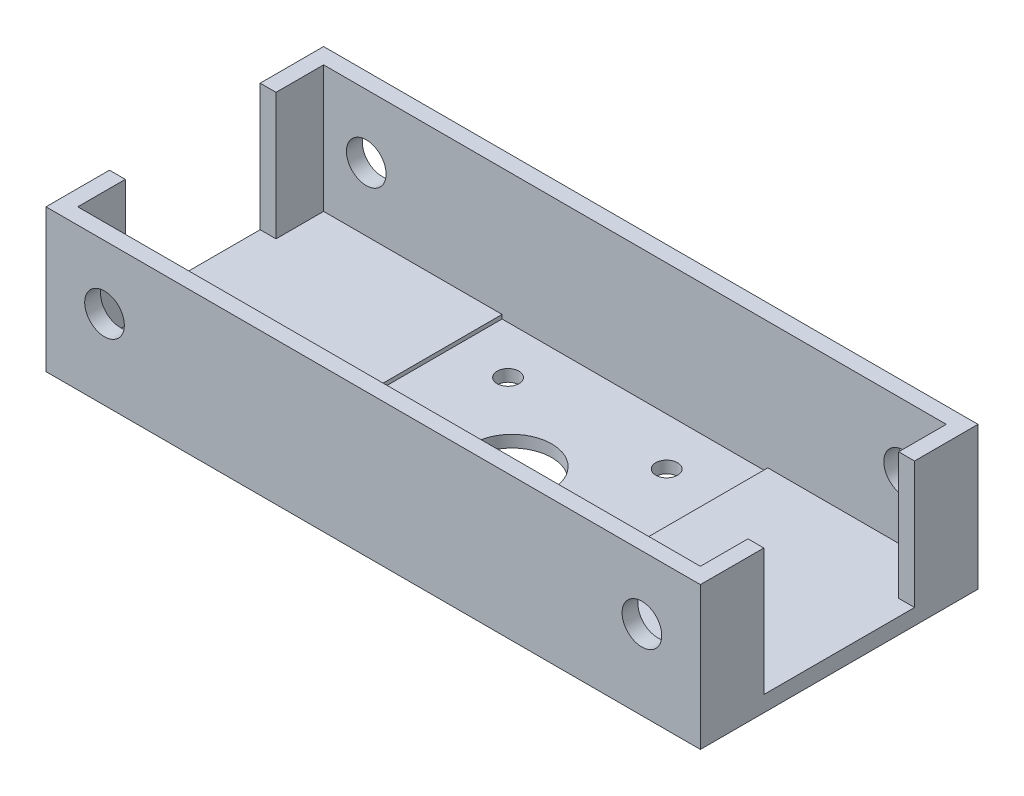
SolidWorks part; units mm, degrees
ref_plane "Front Plane" through (0, 0, 0) normal (0, 0, 1) x (1, 0, 0)
ref_plane "Top Plane" through (0, 0, 0) normal (0, 1, 0) x (1, 0, 0)
ref_plane "Right Plane" through (0, 0, 0) normal (1, 0, 0) x (0, 0, -1)
sketch "Sketch1" plane through (0, 0, 0) normal (0, 1, 0) x (1, 0, 0)
  line L0 (0, 0) -> (0, -14.43) construction
  line L1 (-37.5, 20) -> (37.5, 20)
  line L2 (-37.5, 20) -> (-37.5, -20)
  line L3 (-37.5, -20) -> (37.5, -20)
  line L4 (37.5, 20) -> (37.5, -20)
  line L5 (-37.5, 20) -> (37.5, -20) construction
  line L6 (-37.5, -20) -> (37.5, 20) construction
  line L7 (0, 0) -> (6.508, 0) construction
  line L8 (-5, 10) -> (5, 10)
  line L9 (-5, 10) -> (-5, -10)
  line L10 (-5, -10) -> (5, -10)
  line L11 (5, 10) -> (5, -10)
  line L12 (-5, 10) -> (5, -10) construction
  line L13 (-5, -10) -> (5, 10) construction
  circle A0 centre (-21, 0) radius 5
  circle A1 centre (-30, 8.25) radius 1.7
  circle A2 centre (-12, 8.25) radius 1.7
  circle A3 centre (-12, -8.25) radius 1.7
  circle A4 centre (-30, -8.25) radius 1.7
  circle A5 centre (12, 8.25) radius 1.7
  circle A6 centre (12, -8.25) radius 1.7
  circle A7 centre (21, 0) radius 5
  circle A8 centre (30, -8.25) radius 1.7
  circle A9 centre (30, 8.25) radius 1.7
  point P0 (0, 0)
  dimension "D3" = 10
  dimension "D4" = 16.5
  dimension "D5" = 16.5
  dimension "D6" = 18
  dimension "D9" = 10
  dimension "D11" = 20
  dimension "D13" = 7.5
  dimension "D17" = 3.4
  dimension "D19" = 11.75
  dimension "D20" = 11.75
  dimension "D1" = 75
  dimension "D2" = 40
  dimension "D10" = 10
  dimension "D7" = 2
  dimension "D8" = 2
extrude "Boss-Extrude1" add sketch "Sketch1" along normal blind 3
sketch "Sketch2" plane through (0, 3, 0) normal (0, 1, 0) x (1, 0, 0)
  line L0 (-37.5, 20) -> (-37.5, -20) construction
  line L1 (-33.5, 14) -> (33.5, 14)
  line L2 (-33.5, 14) -> (-33.5, -14)
  line L3 (-33.5, -14) -> (33.5, -14)
  line L4 (33.5, 14) -> (33.5, -14)
  line L5 (37.5, -20) -> (37.5, 20) construction
  line L6 (37.5, 20) -> (-37.5, 20) construction
  line L7 (-37.5, -20) -> (37.5, -20) construction
  dimension "D1" = 4
  dimension "D2" = 4
  dimension "D3" = 6
  dimension "D4" = 6
extrude "Cut-Extrude1" cut sketch "Sketch2" against normal through all both and the other way through all
sketch "Sketch3" plane through (0, 3, 0) normal (0, 1, 0) x (1, 0, 0)
  line L1 (37.5, 20) -> (-37.5, 20)
  line L2 (37.5, 20) -> (37.5, 35)
  line L3 (37.5, 35) -> (-37.5, 35)
  line L4 (-37.5, 20) -> (-37.5, 35)
  line L5 (-37.5, -20) -> (37.5, -20)
  line L6 (-37.5, -20) -> (-37.5, -35)
  line L7 (-37.5, -35) -> (37.5, -35)
  line L8 (37.5, -20) -> (37.5, -35)
  line L10 (-37.5, 20) -> (-33.5, 20)
  line L11 (-37.5, 20) -> (-37.5, -20)
  line L12 (-37.5, -20) -> (-33.5, -20)
  line L13 (-33.5, 20) -> (-33.5, -20)
  line L14 (37.5, 20) -> (33.5, 20)
  line L15 (37.5, 20) -> (37.5, -20)
  line L16 (37.5, -20) -> (33.5, -20)
  line L17 (33.5, 20) -> (33.5, -20)
  line M3 (-33.5, -14) -> (-33.5, 14)
  line M5 (33.5, 14) -> (33.5, -14)
  line M11 (37.5, -20) -> (37.5, 20)
  line M12 (37.5, 20) -> (-37.5, 20)
  line M13 (-37.5, 20) -> (-37.5, -20)
  line M14 (-37.5, -20) -> (37.5, -20)
  dimension "D1" = 15
  dimension "D2" = 15
extrude "Boss-Extrude3" add sketch "Sketch3" along normal blind 110 and the other way blind 3 contours L8 L5 L6 L7 M14 | L4 L1 L2 L3 M12 | L17 M12 M5 M14 M11 | L13 L1 M13 M14 M3
sketch "Sketch6" plane through (0, 3, 0) normal (0, 1, 0) x (1, 0, 0)
  line L0 (-37.5, -35) -> (37.5, -35) construction
  line L1 (-33.5, -20) -> (33.5, -20)
  line L2 (-33.5, -20) -> (-33.5, -31)
  line L3 (-33.5, -31) -> (33.5, -31)
  line L4 (33.5, -20) -> (33.5, -31)
  line L5 (33.5, 20) -> (-33.5, 20)
  line L6 (33.5, 20) -> (33.5, 31)
  line L7 (33.5, 31) -> (-33.5, 31)
  line L8 (-33.5, 20) -> (-33.5, 31)
  line L9 (37.5, 35) -> (-37.5, 35) construction
  dimension "D1" = 4
  dimension "D2" = 4
extrude "Cut-Extrude4" cut sketch "Sketch6" along normal through all
sketch "Sketch7" plane through (-37.5, 0, 0) normal (-1, 0, 0) x (0, 0, 1)
  line L0 (35, 0) -> (35, 113) construction
  line L1 (-35, 113) -> (35, 113)
  line L2 (-35, 113) -> (-35, 76)
  line L3 (-35, 76) -> (35, 76)
  line L4 (35, 113) -> (35, 76)
  dimension "D1" = 37
extrude "Boss-Extrude4" add sketch "Sketch7" along normal blind 45
ref_plane "Plane1" through (0, 0, 0) normal (1, 0, 0) x (0, 0, -1)
mirror "Mirror2" about plane through (0, 0, 0) normal (1, 0, 0) of "Boss-Extrude4"
sketch "Sketch8" plane through (0, 113, 0) normal (0, 1, 0) x (1, 0, 0)
  line L0 (-82.5, -35) -> (-82.5, 35) construction
  line L1 (-33.5, 31) -> (-78.5, 31)
  line L2 (-33.5, 31) -> (-33.5, -31)
  line L3 (-33.5, -31) -> (-78.5, -31)
  line L4 (-78.5, 31) -> (-78.5, -31)
  line L5 (33.5, -31) -> (78.5, -31)
  line L6 (33.5, -31) -> (33.5, 31)
  line L7 (33.5, 31) -> (78.5, 31)
  line L8 (78.5, -31) -> (78.5, 31)
  line L9 (82.5, -35) -> (82.5, 35) construction
  dimension "D1" = 4
  dimension "D2" = 4
extrude "Cut-Extrude6" cut sketch "Sketch8" against normal blind 29
sketch "Sketch9" plane through (-82.5, 0, 0) normal (-1, 0, 0) x (0, 0, 1)
  line L18 (-31, 84) -> (31, 84) construction
  line L19 (-19, 84) -> (19, 84)
  line L20 (-19, 84) -> (-19, 112.5)
  line L21 (-19, 112.5) -> (19, 112.5)
  line L22 (19, 84) -> (19, 112.5)
  line L25 (-31, 84) -> (-31, 113) construction
  dimension "D1" = 38
  dimension "D2" = 12
  dimension "D3" = 28.5
sketch "Sketch11" plane through (0, 0, 35) normal (0, 0, 1) x (1, 0, 0)
  line L0 (82.5, 76) -> (82.5, 113) construction
  line L1 (-82.5, 76) -> (-37.5, 76)
  line L2 (-82.5, 76) -> (-82.5, 80)
  line L3 (-82.5, 80) -> (-37.5, 80)
  line L4 (-37.5, 76) -> (-37.5, 80)
  line L5 (37.5, 76) -> (82.5, 76)
  line L6 (37.5, 76) -> (37.5, 80)
  line L7 (37.5, 80) -> (82.5, 80)
  line L8 (82.5, 76) -> (82.5, 80)
  line L11 (-78.5, 84) -> (-33.5, 84) construction
  line L12 (33.5, 84) -> (78.5, 84) construction
  dimension "D1" = 4
  dimension "D2" = 4
extrude "Cut-Extrude9" cut sketch "Sketch11" against normal through all
extrude "Cut-Extrude10" cut sketch "Sketch9" against normal through all
sketch "Sketch13" plane through (0, 84, 0) normal (0, 1, 0) x (1, 0, 0)
  line L0 (-78.5, 31) -> (-78.5, -31) construction
  line L1 (-57, 19) -> (-52, 19)
  line L2 (-57, 19) -> (-57, -19)
  line L3 (-57, -19) -> (-52, -19)
  line L4 (-52, 19) -> (-52, -19)
  line L7 (78.5, 31) -> (-78.5, 31) construction
  line L13 (-57, -19) -> (-57, 19)
  line L17 (-82.5, -19) -> (-107.5, -19)
  line L18 (-82.5, -19) -> (-82.5, 19)
  line L19 (-82.5, 19) -> (-107.5, 19)
  line L20 (-107.5, -19) -> (-107.5, 19)
  line L21 (-107.5, 19) -> (-61, 19)
  line L22 (-107.5, 19) -> (-107.5, -19)
  line L23 (-107.5, -19) -> (-61, -19)
  line L24 (-61, 19) -> (-61, -19)
  dimension "D1" = 21.5
  dimension "D2" = 5
  dimension "D3" = 38
  dimension "D4" = 12
  dimension "D5" = 25
  dimension "D6" = 46.5
extrude "Boss-Extrude5" add sketch "Sketch13" along normal blind 32 contours L4 L1 L2 L3
sketch "Sketch14" plane through (-57, 0, 0) normal (-1, 0, 0) x (0, 0, 1)
  line L0 (-19, 116) -> (-19, 84) construction
  line L4 (19, 112.5) -> (-19, 112.5) construction
  circle A0 centre (0, 98.25) radius 5
  circle A1 centre (-9, 106.5) radius 1.7
  circle A2 centre (9, 106.5) radius 1.7
  circle A3 centre (9, 90) radius 1.7
  circle A4 centre (-9, 90) radius 1.7
  dimension "D1" = 19
  dimension "D2" = 9
  dimension "D3" = 10
  dimension "D6" = 3.4
  dimension "D7" = 14.25
  dimension "D8" = 16.5
  dimension "D9" = 18
  dimension "D10" = 8.25
  dimension "D4" = 2
  dimension "D5" = 2
extrude "Cut-Extrude11" cut sketch "Sketch14" against normal blind 32
mirror "Mirror4" about plane through (0, 0, 0) normal (1, 0, 0) of "Boss-Extrude5", "Cut-Extrude11"
sketch "Sketch15" plane through (0, 113, 0) normal (0, 1, 0) x (1, 0, 0)
  line L1 (-82.5, 35) -> (82.5, 35)
  line L2 (-82.5, 35) -> (-82.5, -35)
  line L3 (-82.5, -35) -> (82.5, -35)
  line L4 (82.5, 35) -> (82.5, -35)
  line L5 (-78.5, 31) -> (78.5, 31)
  line L6 (-78.5, 31) -> (-78.5, -31)
  line L7 (-78.5, -31) -> (78.5, -31)
  line L8 (78.5, 31) -> (78.5, -31)
extrude "Boss-Extrude6" add sketch "Sketch15" along normal blind 3
sketch "Sketch16" plane through (0, 0, 35) normal (0, 0, 1) x (1, 0, 0)
  line L1 (-10, 14.0464) -> (10, 14.0464)
  line L2 (-10, 14.0464) -> (-10, 9.2258)
  line L3 (-10, 9.2258) -> (10, 9.2258)
  line L4 (10, 14.0464) -> (10, 9.2258)
  line L5 (-37.5, 0) -> (-37.5, 80) construction
  dimension "D1" = 20
  dimension "D2" = 27.5
extrude "Cut-Extrude12" cut sketch "Sketch16" against normal through all
sketch "Sketch18" plane through (0, 0, 35) normal (0, 0, 1) x (1, 0, 0)
  line L0 (57, 116) -> (57, 84) construction
  line L2 (33.5, 84) -> (78.5, 84) construction
  circle A0 centre (67.75, 100) radius 5
  dimension "D1" = 10.75
  dimension "D2" = 16
  dimension "D3" = 10
extrude "Cut-Extrude14" cut sketch "Sketch18" against normal through all
mirror "Mirror5" about plane through (0, 0, 0) normal (1, 0, 0) of "Cut-Extrude14"
mirror "Mirror6" about plane through (0, 116, 0) normal (0, 1, 0) of "Mirror4", "Boss-Extrude5", "Cut-Extrude11"
sketch "Sketch19" plane through (82.5, 0, 0) normal (1, 0, 0) x (0, 0, -1)
  line L0 (19, 148) -> (19, 84) construction
  line L1 (-19, 112.5) -> (19, 112.5)
  line L2 (-19, 112.5) -> (-19, 116)
  line L3 (-19, 116) -> (19, 116)
  line L4 (19, 112.5) -> (19, 116)
extrude "Cut-Extrude15" cut sketch "Sketch19" against normal blind 10
mirror "Mirror7" about plane through (0, 0, 0) normal (1, 0, 0) of "Cut-Extrude15"
sketch "Sketch20" plane through (0, 3, 0) normal (0, 1, 0) x (1, 0, 0)
  line L0 (33.5, 31) -> (-33.5, 31) construction
  line L1 (-5, -10) -> (5, -10)
  line L2 (-5, -10) -> (-5, 10)
  line L3 (-5, 10) -> (5, 10)
  line L4 (5, -10) -> (5, 10)
  line L5 (-5, -10) -> (5, 10) construction
  line L6 (-5, 10) -> (5, -10) construction
  line L7 (0, 0) -> (0, 17.5) construction
  line L8 (-37.5, 20) -> (37.5, 20)
  line L9 (-37.5, 20) -> (-37.5, -20)
  line L10 (-37.5, -20) -> (37.5, -20)
  line L11 (37.5, 20) -> (37.5, -20)
  line L12 (-37.5, 20) -> (37.5, -20) construction
  line L13 (-37.5, -20) -> (37.5, 20) construction
  line L14 (0, -34.1) -> (0, 34.1) construction
  circle A1 centre (-12, 17.5) radius 1.2
  circle A2 centre (-12, -17.5) radius 1.2
  circle A3 centre (-24, -17.5) radius 1.2
  circle A4 centre (-24, 17.5) radius 1.2
  circle A5 centre (12, -17.5) radius 1.2
  circle A6 centre (24, -17.5) radius 1.2
  circle A7 centre (12, 17.5) radius 1.2
  circle A8 centre (24, 17.5) radius 1.2
  point P2 (0, 0)
  point P10 (0, 0)
  dimension "D1" = 7
  dimension "D2" = 10
  dimension "D4" = 2.5
  dimension "D7" = 35
  dimension "D8" = 7
  dimension "D9" = 2.4
  dimension "D11" = 12
  dimension "D3" = 21
  dimension "D5" = 75
  dimension "D6" = 40
  dimension "D10" = 2
extrude "Cut-Extrude16" cut sketch "Sketch20" against normal blind 10 contours A4 | A1 | A7 | A3 | A2 | A8 | A5 | A6
sketch "Sketch21" plane through (0, 0, 35) normal (0, 0, 1) x (1, 0, 0)
  line L0 (0, -34.1) -> (0, 34.1) construction
  line L1 (37.5, 0) -> (27.5, 0)
  line L2 (37.5, 0) -> (37.5, 80)
  line L3 (37.5, 80) -> (27.5, 80)
  line L4 (27.5, 0) -> (27.5, 80)
  line L5 (-27.5, 0) -> (-27.5, 80)
  line L6 (-37.5, 80) -> (-27.5, 80)
  line L7 (-37.5, 0) -> (-37.5, 80)
  line L8 (-37.5, 0) -> (-27.5, 0)
  dimension "D1" = 10
  dimension "D2" = 80
extrude "Cut-Extrude17" cut sketch "Sketch21" against normal through all
sketch "Sketch22" plane through (0, 0, 35) normal (0, 0, 1) x (1, 0, 0)
  line L1 (-27.5, 0) -> (27.5, 0)
  line L2 (-27.5, 0) -> (-27.5, 80)
  line L3 (-27.5, 80) -> (27.5, 80)
  line L4 (27.5, 0) -> (27.5, 80)
extrude "Cut-Extrude18" cut sketch "Sketch22" against normal through all
sketch "Sketch23" plane through (0, 80, 0) normal (0, -1, 0) x (1, 0, 0)
  line L1 (-33.5, 31) -> (33.5, 31)
  line L2 (-33.5, 31) -> (-33.5, -31)
  line L3 (-33.5, -31) -> (33.5, -31)
  line L4 (33.5, 31) -> (33.5, -31)
extrude "Boss-Extrude7" add sketch "Sketch23" against normal blind 3
sketch "Sketch24" plane through (0, 83, 0) normal (0, 1, 0) x (1, 0, 0)
  line L5 (78.5, 31) -> (-78.5, 31) construction
  line L9 (33.5, -31) -> (-33.5, -31) construction
  line L10 (0, 0) -> (0, 16.8876) construction
  line L11 (0, -34.1) -> (0, 34.1) construction
  circle A0 centre (0, 0) radius 10
  circle A1 centre (-20, 19) radius 2.75
  circle A2 centre (-20, -19) radius 2.75
  circle A3 centre (20, -19) radius 2.75
  circle A4 centre (20, 19) radius 2.75
  dimension "D1" = 20
  dimension "D2" = 12
  dimension "D3" = 20
  dimension "D4" = 12
extrude "Cut-Extrude19" cut sketch "Sketch24" against normal through all
sketch "Sketch25" plane through (57, 0, 0) normal (1, 0, 0) x (0, 0, -1)
  line L1 (-19, 148) -> (19, 148)
  line L2 (-19, 148) -> (-19, 84)
  line L3 (-19, 84) -> (19, 84)
  line L4 (19, 148) -> (19, 84)
extrude "Cut-Extrude20" cut sketch "Sketch25" against normal blind 115
